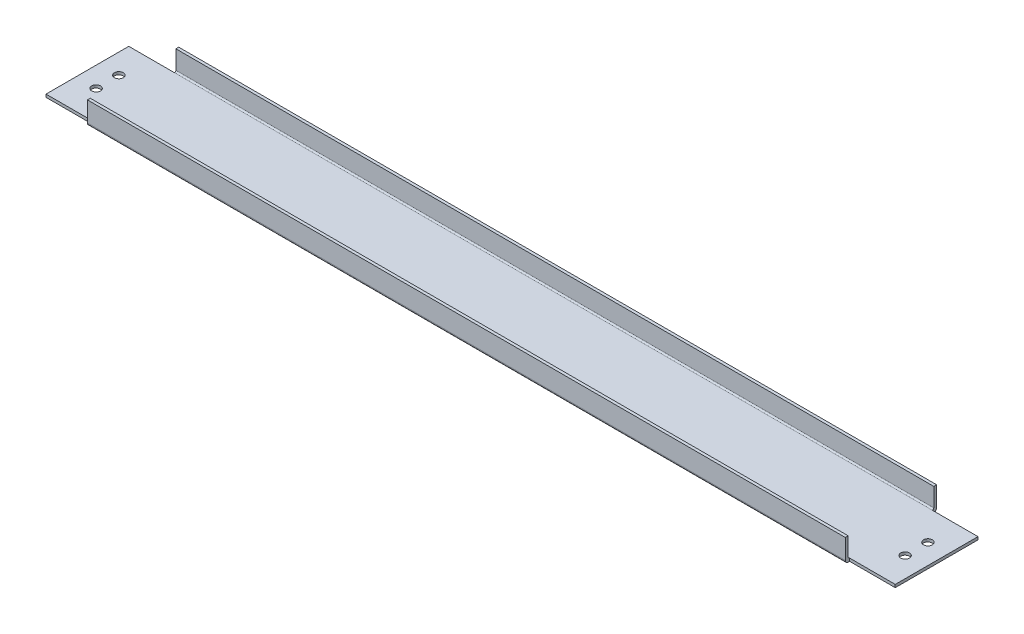
SolidWorks part; units mm, degrees
ref_plane "Front Plane" through (0, 0, 0) normal (0, 0, 1) x (1, 0, 0)
ref_plane "Top Plane" through (0, 0, 0) normal (0, 1, 0) x (1, 0, 0)
ref_plane "Right Plane" through (0, 0, 0) normal (1, 0, 0) x (0, 0, -1)
sketch "Sketch1" plane through (0, 0, 0) normal (1, 0, 0) x (0, 0, -1)
  line L0 (-23.8125, 0) -> (23.8125, 0)
  line L1 (-23.0187, 1.5875) -> (23.0187, 1.5875)
  line L2 (-25.4, 1.5875) -> (-25.4, 12.7)
  line L3 (-23.8125, 2.3813) -> (-23.8125, 12.7)
  line L4 (-23.8125, 12.7) -> (-25.4, 12.7)
  line L5 (23.8125, 2.3813) -> (23.8125, 12.7)
  line L6 (23.8125, 12.7) -> (25.4, 12.7)
  line L7 (25.4, 12.7) -> (25.4, 1.5875)
  arc A0 (23.8125, 0) -> (25.4, 1.5875) centre (23.8125, 1.5875) ccw
  arc A1 (-23.8125, 0) -> (-25.4, 1.5875) centre (-23.8125, 1.5875) cw
  arc A2 (-23.0187, 1.5875) -> (-23.8125, 2.3813) centre (-23.0188, 2.3813) cw
  arc A3 (23.8125, 2.3813) -> (23.0187, 1.5875) centre (23.0188, 2.3813) cw
  point P4 (0, 0)
  point P13 (25.4, 0)
  point P16 (-25.4, 0)
  dimension "D5" = 1.5875
  dimension "D6" = 0.7937
  dimension "D7" = 0.7937
  dimension "D1" = 50.8
  dimension "D2" = 1.5875
  dimension "D3" = 1.5875
  dimension "D4" = 12.7
extrude "Boss-Extrude1" add sketch "Sketch1" along normal blind 210.82
sketch "Sketch2" plane through (210.82, 0, 0) normal (1, 0, 0) x (0, 0, -1)
  line L0 (-23.0187, 1.5875) -> (-23.0188, 0)
  line L1 (-23.8125, 0) -> (23.8125, 0) construction
  line L2 (-23.0188, 0) -> (23.0188, 0)
  line L3 (23.0188, 0) -> (23.0188, 1.5875)
  line L4 (23.0187, 1.5875) -> (-23.0187, 1.5875) construction
  line L5 (23.0188, 1.5875) -> (-23.0187, 1.5875)
  arc A0 (23.0187, 1.5875) -> (23.8125, 2.3813) centre (23.0188, 2.3813) ccw construction
extrude "Boss-Extrude2" add sketch "Sketch2" along normal blind 25.4
sketch "Sketch3" plane through (0, 1.5875, 0) normal (0, 1, 0) x (1, 0, 0)
  line L0 (0, 0) -> (225.044, 0) construction
  line L1 (225.044, 6.35) -> (225.044, -6.35) construction
  line L2 (236.22, 23.0188) -> (236.22, -23.0187) construction
  line L3 (236.22, 23.0188) -> (210.82, 23.0187) construction
  circle A0 centre (225.044, -6.35) radius 0.635
  circle A1 centre (225.044, 6.35) radius 0.635
  point P6 (225.044, 0)
  dimension "D3" = 1.27
  dimension "D1" = 225.044
  dimension "D2" = 12.7
  dimension "D4" = 11.176
  dimension "D5" = 16.6688
mirror "Mirror1" about plane through (0, 0, 0) normal (1, 0, 0) of "Boss-Extrude2", "Boss-Extrude1"
extrude "Cut-Extrude1" cut sketch "Sketch3" against normal through all
hole_wizard "#8 Clearance Hole1" positions "Sketch5" profile "Sketch4" hole size "#8" standard "ANSI Inch" end condition through all
sketch "Sketch5" plane through (0, 1.5875, 0) normal (0, 1, 0) x (1, 0, 0)
  point P0 (225.044, -6.35)
  point P3 (225.044, 6.35)
sketch "Sketch4" plane through (225.044, 1.5875, 6.35) normal (1, 0, 0) x (0, 0, 1)
  line L0 (0, 0) -> (0, 1.5876)
  line L1 (0, 1.5876) -> (2.4574, 1.5876)
  line L2 (2.4574, 1.5876) -> (2.4574, 0)
  line L5 (2.4574, 0) -> (0, 0)
  line L11 (0, -6.35) -> (0, 107.95) construction
  dimension "Thru Hole Dia." = 4.9149
  dimension "Thru Hole Depth" = 1.5876
mirror "Mirror2" about plane through (0, 0, 0) normal (1, 0, 0) of "#8 Clearance Hole1"
